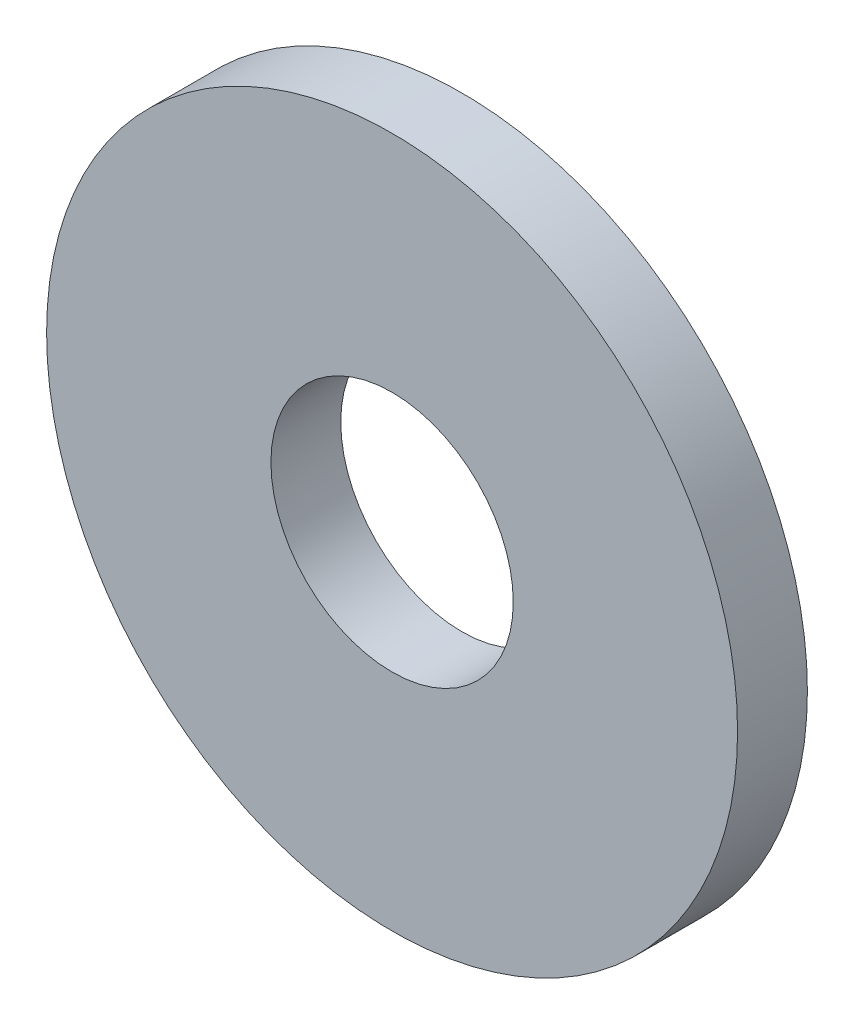
SolidWorks part; units mm, degrees
ref_plane "Front Plane" through (0, 0, 0) normal (0, 0, 1) x (1, 0, 0)
ref_plane "Top Plane" through (0, 0, 0) normal (0, 1, 0) x (1, 0, 0)
ref_plane "Right Plane" through (0, 0, 0) normal (1, 0, 0) x (0, 0, -1)
sketch "Sketch1" plane through (0, 0, 0) normal (0, 0, 1) x (1, 0, 0)
  circle A0 centre (0, 0) radius 8.412
  circle A1 centre (0, 0) radius 2.95
  dimension "D1" = 5.9
  dimension "D2" = 16.8239
extrude "Boss-Extrude1" add sketch "Sketch1" along normal blind 1.7
sketch "Sketch2" plane through (0, 0, 1.7) normal (0, 0, 1) x (1, 0, 0)
  circle A0 centre (0, 10) radius 2.5
  dimension "D1" = 5
  dimension "D2" = 10
extrude "Cut-Extrude1" [suppressed] cut sketch "Sketch2" against normal through all
equation "\"smallPulleyTeeth\"= 15"
equation "\"largePulleyTeeth\"= 30"
equation "\"eighthThick\"= 2.9mm"
equation "\"sixteenthThick\" = 1.7mm"
equation "\"quarterThick\"=5.9mm"
equation "\"OD\" = 145mm"
equation "\"puckAngle\" = 60.5deg"
equation "\"puckDiam\" = 76.5mm"
equation "\"axlePress\" = 5.9mm"
equation "\"D1@Sketch1\"=\"axlePress\""
equation "\"D1@Boss-Extrude1\"=\"sixteenthThick\""
equation "\"press\" = 0.2mm"
equation "\"wheelClear\" = 0.3mm"
equation "\"10-32clear\" = 4.5mm"
equation "\"6-32clear\" = 3.3mm"
equation "\"8-32clear\" = 4.0mm"
equation "\"4-40clear\" = 2.55mm"
equation "\"wheelHeight\" = 21mm"
equation "\"wheelWell\" = 62mm"
equation "\"D2@Sketch1\"=\"smallPulleyTeeth\" * 3 / pi + 2.5"
